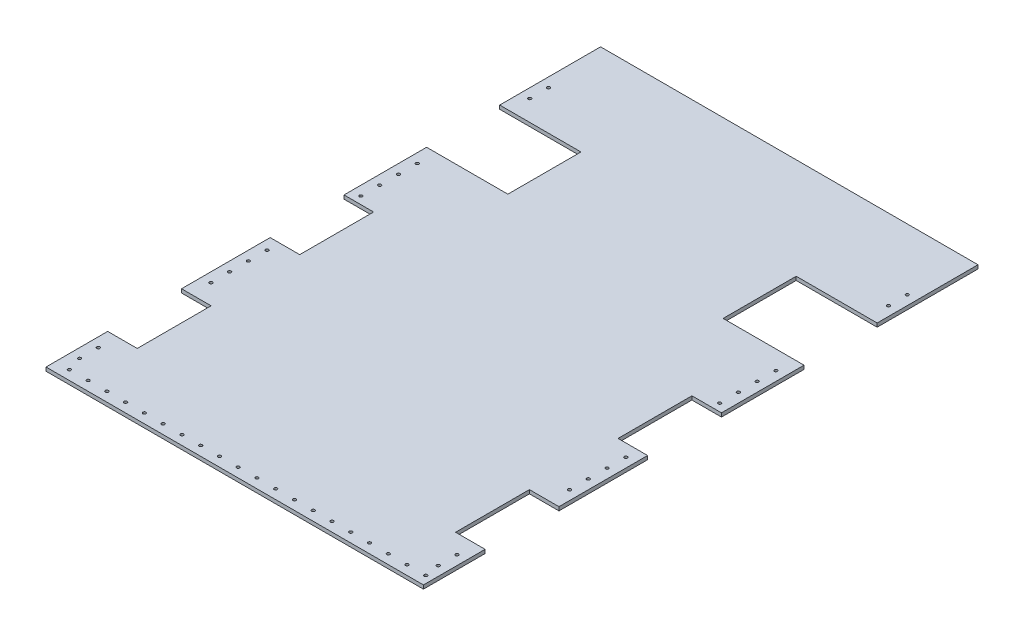
SolidWorks part; units mm, degrees
material "Poliol de poliéter"
ref_plane "Alzado" through (0, 0, 0) normal (0, 0, 1) x (1, 0, 0)
ref_plane "Planta" through (0, 0, 0) normal (0, 1, 0) x (1, 0, 0)
ref_plane "Vista lateral" through (0, 0, 0) normal (1, 0, 0) x (0, 0, -1)
sketch "Croquis1" plane through (0, 0, 0) normal (0, 1, 0) x (1, 0, 0)
  line L1 (255.5, 352.9) -> (-255.5, 352.9)
  line L2 (255.5, 352.9) -> (255.5, -352.9)
  line L3 (255.5, -352.9) -> (-255.5, -352.9)
  line L4 (-255.5, 352.9) -> (-255.5, -352.9)
  line L5 (255.5, 352.9) -> (-255.5, -352.9) construction
  line L6 (255.5, -352.9) -> (-255.5, 352.9) construction
  point P0 (0, 0)
  dimension "D1" = 511
  dimension "D2" = 705.8
extrude "Saliente-Extruir1" add sketch "Croquis1" along normal blind 5
sketch "Croquis2" plane through (0, 0, 0) normal (0, -1, 0) x (-1, 0, 0)
  line L0 (255.5, 352.9) -> (255.5, -352.9) construction
  line L1 (255.5, -269.4013) -> (215.5, -269.4013)
  line L2 (255.5, -269.4013) -> (255.5, -169.4013)
  line L3 (255.5, -169.4013) -> (215.5, -169.4013)
  line L4 (215.5, -269.4013) -> (215.5, -169.4013)
  line L5 (-215.5, -269.4013) -> (-215.5, -169.4013)
  line L6 (-215.5, -269.4013) -> (-255.5, -269.4013)
  line L7 (-255.5, -269.4013) -> (-255.5, -169.4013)
  line L8 (-215.5, -169.4013) -> (-255.5, -169.4013)
  line L9 (255.5, -49.4013) -> (255.5, 50.5987)
  line L10 (255.5, -49.4013) -> (215.5, -49.4013)
  line L11 (215.5, -49.4013) -> (215.5, 50.5987)
  line L12 (255.5, 50.5987) -> (215.5, 50.5987)
  line L13 (-215.5, -49.4013) -> (-215.5, 50.5987)
  line L14 (-215.5, 50.5987) -> (-255.5, 50.5987)
  line L15 (-255.5, -49.4013) -> (-255.5, 50.5987)
  line L16 (-215.5, -49.4013) -> (-255.5, -49.4013)
  dimension "D1" = 40
  dimension "D2" = 100
  dimension "D3" = 2
  dimension "D4" = 2
extrude "Cortar-Extruir1" cut sketch "Croquis2" against normal blind 10
sketch "Croquis4" plane through (0, 0, 0) normal (0, -1, 0) x (-1, 0, 0)
  line L0 (255.5, 352.9) -> (255.5, 50.5987) construction
  line L1 (255.5, 162.4) -> (145.5, 162.4)
  line L2 (255.5, 162.4) -> (255.5, 261.3508)
  line L3 (255.5, 261.3508) -> (145.5, 261.3508)
  line L4 (145.5, 162.4) -> (145.5, 261.3508)
  line L5 (102.4913, 261.0642) -> (159.7413, 261.4458) construction
  line L6 (-145.9, 162.4) -> (-145.9, 261.3508)
  line L7 (-145.9, 162.4) -> (-255.9, 162.4)
  line L8 (-255.9, 162.4) -> (-255.9, 261.3508)
  line L9 (-145.9, 261.3508) -> (-255.9, 261.3508)
  dimension "D1" = 110
extrude "Cortar-Extruir3" cut sketch "Croquis4" against normal blind 10
sketch "Croquis7" plane through (0, 0, 0) normal (0, -1, 0) x (-1, 0, 0)
  circle A0 centre (236.6, -340.2) radius 2.07
  circle A1 centre (211.2, -340.2) radius 2.07
  circle A2 centre (185.8, -340.2) radius 2.07
  circle A3 centre (160.4, -340.2) radius 2.07
  circle A4 centre (135, -340.2) radius 2.07
  circle A5 centre (109.6, -340.2) radius 2.07
  circle A6 centre (84.2, -340.2) radius 2.07
  circle A7 centre (58.8, -340.2) radius 2.07
  circle A8 centre (33.4, -340.2) radius 2.07
  circle A9 centre (8, -340.2) radius 2.07
  circle A10 centre (-17.4, -340.2) radius 2.07
  circle A11 centre (-42.8, -340.2) radius 2.07
  circle A12 centre (-68.2, -340.2) radius 2.07
  circle A13 centre (-93.6, -340.2) radius 2.07
  circle A14 centre (-119, -340.2) radius 2.07
  circle A15 centre (-144.4, -340.2) radius 2.07
  circle A16 centre (-169.8, -340.2) radius 2.07
  circle A17 centre (-195.2, -340.2) radius 2.07
  circle A18 centre (-220.6, -340.2) radius 2.07
  circle A19 centre (-246, -340.2) radius 2.07
  circle A20 centre (242.8, -320.2) radius 2.07
  circle A21 centre (242.8, -294.8) radius 2.07
  circle A27 centre (242.8, -142.4) radius 2.07
  circle A28 centre (242.8, -117) radius 2.07
  circle A29 centre (242.8, -91.6) radius 2.07
  circle A30 centre (242.8, -66.2) radius 2.07
  circle A35 centre (242.8, 60.8) radius 2.07
  circle A36 centre (242.8, 86.2) radius 2.07
  circle A37 centre (242.8, 111.6) radius 2.07
  circle A38 centre (242.8, 137) radius 2.07
  circle A44 centre (242.8, 289.4) radius 2.07
  circle A45 centre (242.8, 314.8) radius 2.07
  circle A46 centre (242.8, -193.2) radius 2.07 [skipped]
  circle A47 centre (242.8, -218.6) radius 2.07 [skipped]
  circle A48 centre (242.8, -244) radius 2.07 [skipped]
  circle A49 centre (242.8, -269.4) radius 2.07 [skipped]
  circle A50 centre (242.8, -167.8) radius 2.07 [skipped]
  circle A51 centre (242.8, 35.4) radius 2.07 [skipped]
  circle A52 centre (242.8, 10) radius 2.07 [skipped]
  circle A53 centre (242.8, -15.4) radius 2.07 [skipped]
  circle A54 centre (242.8, -40.8) radius 2.07 [skipped]
  circle A55 centre (242.8, 238.6) radius 2.07 [skipped]
  circle A56 centre (242.8, 213.2) radius 2.07 [skipped]
  circle A57 centre (242.8, 187.8) radius 2.07 [skipped]
  circle A58 centre (242.8, 162.4) radius 2.07 [skipped]
  circle A59 centre (242.8, 264) radius 2.07 [skipped]
  dimension "D1" = 20
  dimension "D2" = 26
extrude "Cortar-Extruir6" cut sketch "Croquis7" against normal blind 10
sketch "Croquis8" plane through (0, 0, 0) normal (0, -1, 0) x (-1, 0, 0)
  circle A0 centre (246, 385.2) radius 2.07
  circle A1 centre (220.6, 385.2) radius 2.07
  circle A2 centre (195.2, 385.2) radius 2.07
  circle A3 centre (169.8, 385.2) radius 2.07
  circle A4 centre (144.4, 385.2) radius 2.07
  circle A5 centre (119, 385.2) radius 2.07
  circle A6 centre (93.6, 385.2) radius 2.07
  circle A7 centre (68.2, 385.2) radius 2.07
  circle A8 centre (42.8, 385.2) radius 2.07
  circle A9 centre (17.4, 385.2) radius 2.07
  circle A10 centre (-8, 385.2) radius 2.07
  circle A11 centre (-33.4, 385.2) radius 2.07
  circle A12 centre (-58.8, 385.2) radius 2.07
  circle A13 centre (-84.2, 385.2) radius 2.07
  circle A14 centre (-109.6, 385.2) radius 2.07
  circle A15 centre (-135, 385.2) radius 2.07
  circle A16 centre (-160.4, 385.2) radius 2.07
  circle A17 centre (-185.8, 385.2) radius 2.07
  circle A18 centre (-211.2, 385.2) radius 2.07
  circle A19 centre (-236.6, 385.2) radius 2.07
  circle A20 centre (-242.8, 314.8) radius 2.07
  circle A21 centre (-242.8, 289.4) radius 2.07
  circle A27 centre (-242.8, 137) radius 2.07
  circle A28 centre (-242.8, 111.6) radius 2.07
  circle A29 centre (-242.8, 86.2) radius 2.07
  circle A30 centre (-242.8, 60.8) radius 2.07
  circle A35 centre (-242.8, -66.2) radius 2.07
  circle A36 centre (-242.8, -91.6) radius 2.07
  circle A37 centre (-242.8, -117) radius 2.07
  circle A38 centre (-242.8, -142.4) radius 2.07
  circle A44 centre (-242.8, -294.8) radius 2.07
  circle A45 centre (-242.8, -320.2) radius 2.07
  circle A46 centre (-242.8, -269.4) radius 2.07 [skipped]
  circle A47 centre (-242.8, -244) radius 2.07 [skipped]
  circle A48 centre (-242.8, -218.6) radius 2.07 [skipped]
  circle A49 centre (-242.8, -193.2) radius 2.07 [skipped]
  circle A50 centre (-242.8, -167.8) radius 2.07 [skipped]
  circle A51 centre (-242.8, 238.6) radius 2.07 [skipped]
  circle A52 centre (-242.8, 213.2) radius 2.07 [skipped]
  circle A53 centre (-242.8, 162.4) radius 2.07 [skipped]
  circle A54 centre (-242.8, 187.8) radius 2.07 [skipped]
  circle A55 centre (-242.8, 264) radius 2.07 [skipped]
  circle A56 centre (-242.8, 35.4) radius 2.07 [skipped]
  circle A57 centre (-242.8, 10) radius 2.07 [skipped]
  circle A58 centre (-242.8, -15.4) radius 2.07 [skipped]
  circle A59 centre (-242.8, -40.8) radius 2.07 [skipped]
  dimension "D1" = 20
  dimension "D2" = 26
extrude "Cortar-Extruir7" cut sketch "Croquis8" against normal blind 10
sketch "Croquis9" plane through (0, 5, 0) normal (0, 1, 0) x (1, 0, 0)
  line L1 (-255.5, 352.9) -> (255.5, 352.9)
  line L2 (-255.5, 352.9) -> (-255.5, 397.9)
  line L3 (-255.5, 397.9) -> (255.5, 397.9)
  line L4 (255.5, 352.9) -> (255.5, 397.9)
  dimension "D1" = 45
extrude "Saliente-Extruir2" add sketch "Croquis9" against normal blind 5
